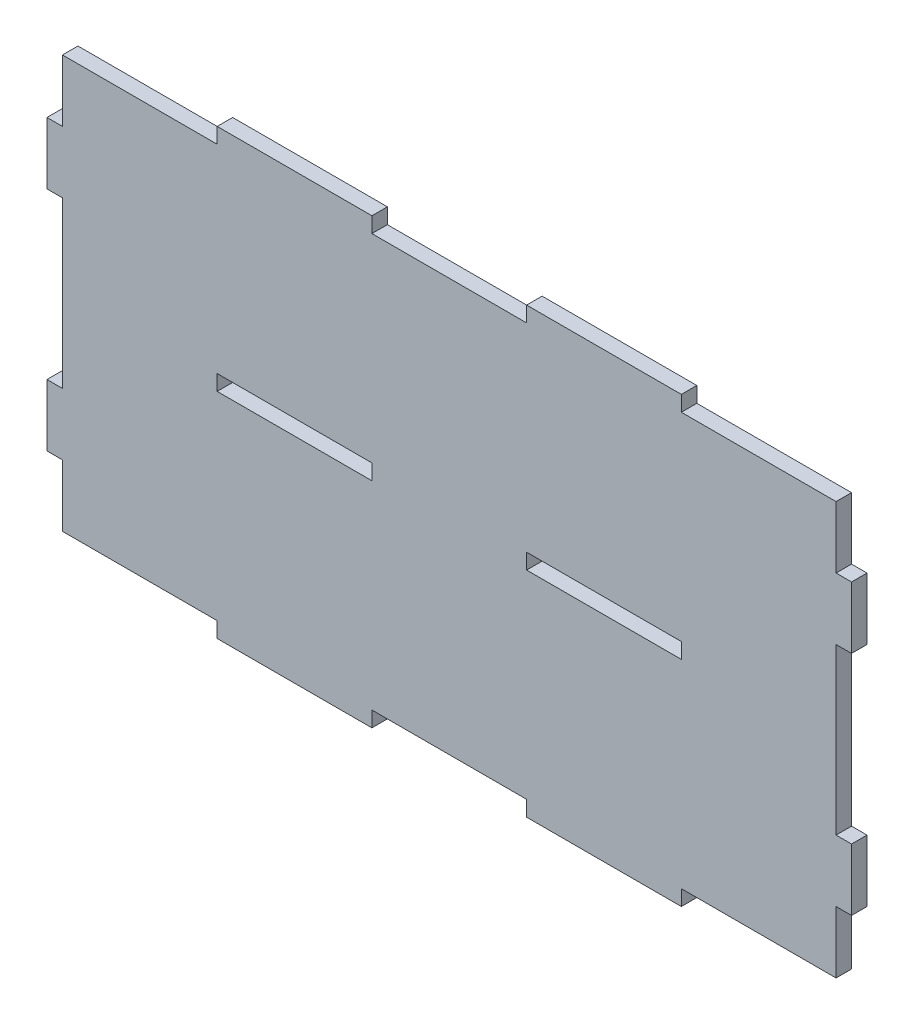
SolidWorks part; units mm, degrees
material "Pinho"
ref_plane "Plano frontal" through (0, 0, 0) normal (0, 0, 1) x (1, 0, 0)
ref_plane "Plano superior" through (0, 0, 0) normal (0, 1, 0) x (1, 0, 0)
ref_plane "Plano direito" through (0, 0, 0) normal (1, 0, 0) x (0, 0, -1)
sketch "Esboço1" plane through (0, 0, 0) normal (0, 0, 1) x (1, 0, 0)
  line L0 (45, 40) -> (75, 40)
  line L1 (-75, -40) -> (-45, -40)
  line L2 (-75, -40) -> (-75, -28)
  line L3 (-75, 40) -> (-45, 40)
  line L4 (75, -40) -> (75, -28)
  line L5 (-75, -40) -> (75, 40) construction
  line L6 (-75, 40) -> (75, -40) construction
  line L8 (-45, 40) -> (-45, 43)
  line L9 (-45, 43) -> (-15, 43)
  line L10 (-15, 40) -> (-15, 43)
  line L11 (-15, -40) -> (15, -40)
  line L12 (45, -40) -> (75, -40)
  line L14 (15, 40) -> (15, 43)
  line L15 (15, 43) -> (45, 43)
  line L16 (45, 40) -> (45, 43)
  line L17 (-15, 40) -> (15, 40)
  line L18 (-75, 28) -> (-75, 40)
  line L20 (-45, -40) -> (-45, -43)
  line L21 (-45, -43) -> (-15, -43)
  line L22 (-15, -40) -> (-15, -43)
  line L23 (-75, 28) -> (-78, 28)
  line L26 (15, -40) -> (15, -43)
  line L27 (15, -43) -> (45, -43)
  line L28 (45, -40) -> (45, -43)
  line L29 (-75, 16) -> (-78, 16)
  line L30 (-78, 28) -> (-78, 16)
  line L31 (-75, -16) -> (-75, 16)
  line L32 (75, -16) -> (75, 16)
  line L33 (-75, -28) -> (-78, -28)
  line L35 (-75, -16) -> (-78, -16)
  line L36 (-78, -28) -> (-78, -16)
  line L37 (75, 16) -> (78, 16)
  line L39 (75, 28) -> (78, 28)
  line L40 (78, 16) -> (78, 28)
  line L41 (75, 0) -> (-76.3343, 0) construction
  line L43 (75, -16) -> (78, -16)
  line L45 (75, -28) -> (78, -28)
  line L46 (78, -16) -> (78, -28)
  line L47 (75, 28) -> (75, 40)
  line L48 (45, 1.5) -> (15, 1.5)
  line L49 (45, 1.5) -> (45, -1.5)
  line L50 (45, -1.5) -> (15, -1.5)
  line L51 (15, 1.5) -> (15, -1.5)
  line L52 (45, 1.5) -> (15, -1.5) construction
  line L53 (45, -1.5) -> (15, 1.5) construction
  line L54 (-15, 1.5) -> (-45, 1.5)
  line L55 (-15, 1.5) -> (-15, -1.5)
  line L56 (-15, -1.5) -> (-45, -1.5)
  line L57 (-45, 1.5) -> (-45, -1.5)
  line L58 (-15, 1.5) -> (-45, -1.5) construction
  line L59 (-15, -1.5) -> (-45, 1.5) construction
  point P0 (0, 0)
  point P35 (30, 0)
  point P45 (-30, 0)
  dimension "D1" = 150
  dimension "D2" = 80
  dimension "D3" = 30
  dimension "D4" = 30
  dimension "D5" = 30
  dimension "D6" = 30
  dimension "D7" = 3
  dimension "D8" = 3
  dimension "D9" = 3
  dimension "D10" = 3
  dimension "D11" = 30
  dimension "D12" = 30
  dimension "D13" = 30
  dimension "D14" = 30
  dimension "D15" = 12
  dimension "D16" = 12
  dimension "D17" = 12
  dimension "D18" = 12
  dimension "D19" = 3
  dimension "D20" = 3
  dimension "D21" = 12
  dimension "D22" = 12
  dimension "D23" = 12
  dimension "D24" = 12
  dimension "D25" = 3
  dimension "D26" = 3
  dimension "D27" = 30
  dimension "D28" = 30
  dimension "D29" = 30
  dimension "D30" = 30
  dimension "D31" = 3
  dimension "D32" = 3
extrude "Ressalto-extrusão1" add sketch "Esboço1" along normal blind 3
